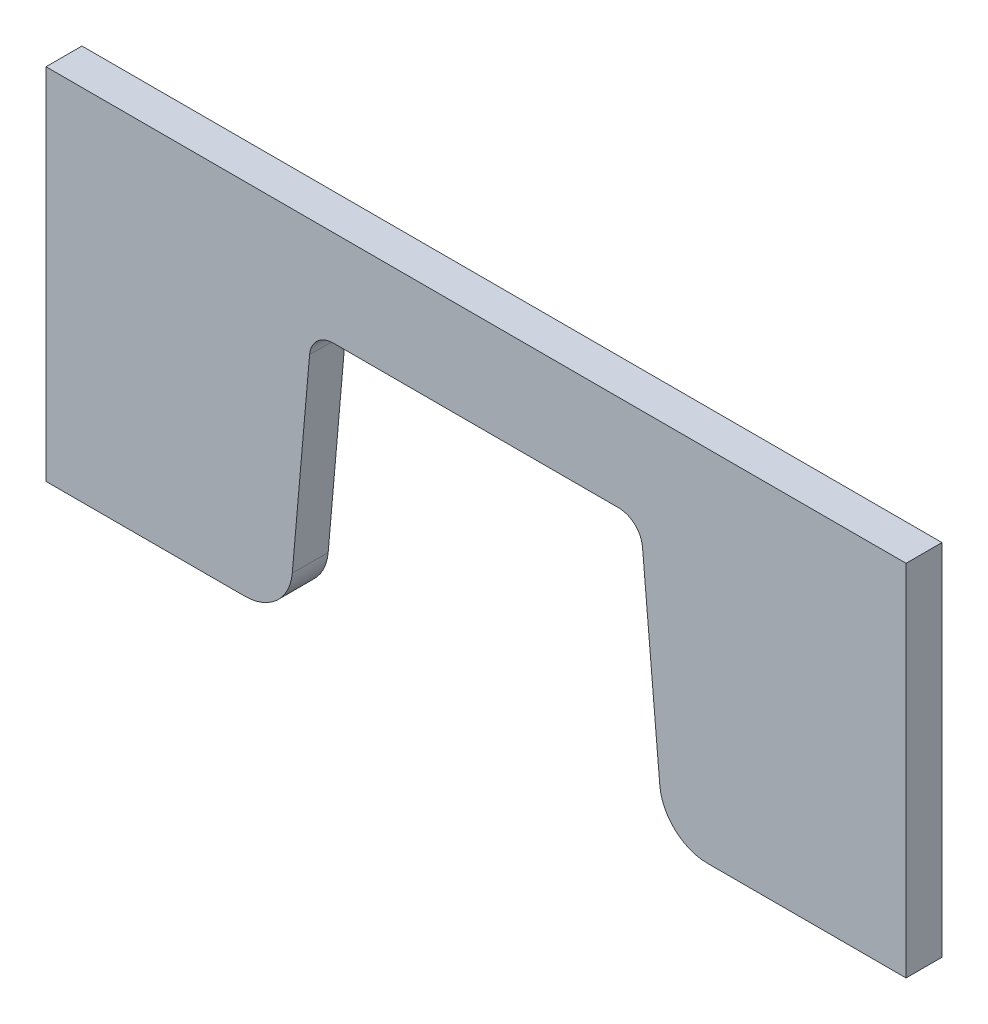
SolidWorks part; units mm, degrees
material "MDF"
ref_plane "Front Plane" through (0, 0, 0) normal (0, 0, 1) x (1, 0, 0)
ref_plane "Top Plane" through (0, 0, 0) normal (0, 1, 0) x (1, 0, 0)
ref_plane "Right Plane" through (0, 0, 0) normal (1, 0, 0) x (0, 0, -1)
sketch "Sketch1" plane through (0, 0, 0) normal (0, 0, 1) x (1, 0, 0)
  line L0 (-228.0888, -463.55) -> (-126.4888, -463.55) construction
  line L1 (-126.4888, -463.55) -> (-122.7761, -463.55) construction
  line L2 (-97.4727, -440.3638) -> (-88.2891, -335.3948) construction
  line L3 (-61.8749, -323.8017) -> (-75.6375, -323.8017) construction
  line L4 (61.8749, -323.8017) -> (-61.8749, -323.8017) construction
  line L5 (61.8749, -323.8017) -> (75.6375, -323.8017) construction
  line L6 (97.4727, -440.3638) -> (88.2891, -335.3948) construction
  line L8 (228.0888, -463.55) -> (126.4888, -463.55) construction
  line L9 (-228.0888, -463.55) -> (-126.4888, -463.55)
  line L10 (-126.4888, -463.55) -> (-122.7761, -463.55)
  line L11 (-97.4727, -440.3638) -> (-88.2891, -335.3948)
  line L12 (-61.8749, -323.8017) -> (-75.6375, -323.8017)
  line L13 (61.8749, -323.8017) -> (-61.8749, -323.8017)
  line L14 (61.8749, -323.8017) -> (75.6375, -323.8017)
  line L15 (97.4727, -440.3638) -> (88.2891, -335.3948)
  line L17 (228.0888, -463.55) -> (122.7761, -463.55)
  line L18 (228.0888, -463.55) -> (228.0888, -273.05)
  line L19 (228.0888, 0) -> (228.0888, -437.7788) construction
  line L20 (228.0888, -273.05) -> (-228.0888, -273.05)
  line L21 (-228.0888, 0) -> (-228.0888, -437.7788) construction
  line L22 (-228.0888, -273.05) -> (-228.0888, -463.55)
  arc A0 (-122.7761, -463.55) -> (-113.7888, -461.9069) centre (-122.7761, -438.15) ccw construction
  arc A1 (-113.7888, -461.9069) -> (-97.4727, -440.3638) centre (-122.7761, -438.15) ccw construction
  arc A2 (-75.6375, -323.8017) -> (-88.2891, -335.3948) centre (-75.6375, -336.5017) ccw construction
  arc A3 (88.2891, -335.3948) -> (75.6375, -323.8017) centre (75.6375, -336.5017) ccw construction
  arc A6 (-122.7761, -463.55) -> (-113.7888, -461.9069) centre (-122.7761, -438.15) ccw
  arc A7 (-113.7888, -461.9069) -> (-97.4727, -440.3638) centre (-122.7761, -438.15) ccw
  arc A8 (-75.6375, -323.8017) -> (-88.2891, -335.3948) centre (-75.6375, -336.5017) ccw
  arc A9 (88.2891, -335.3948) -> (75.6375, -323.8017) centre (75.6375, -336.5017) ccw
  arc A10 (97.4727, -440.3638) -> (122.7761, -463.55) centre (122.7761, -438.15) ccw
  point P2 (121.5407, -463.55)
  point P19 (123.1763, -463.55)
  dimension "D2" = 25.4
  dimension "D1" = 190.5
extrude "Boss-Extrude1" add sketch "Sketch1" along normal blind 19.05
